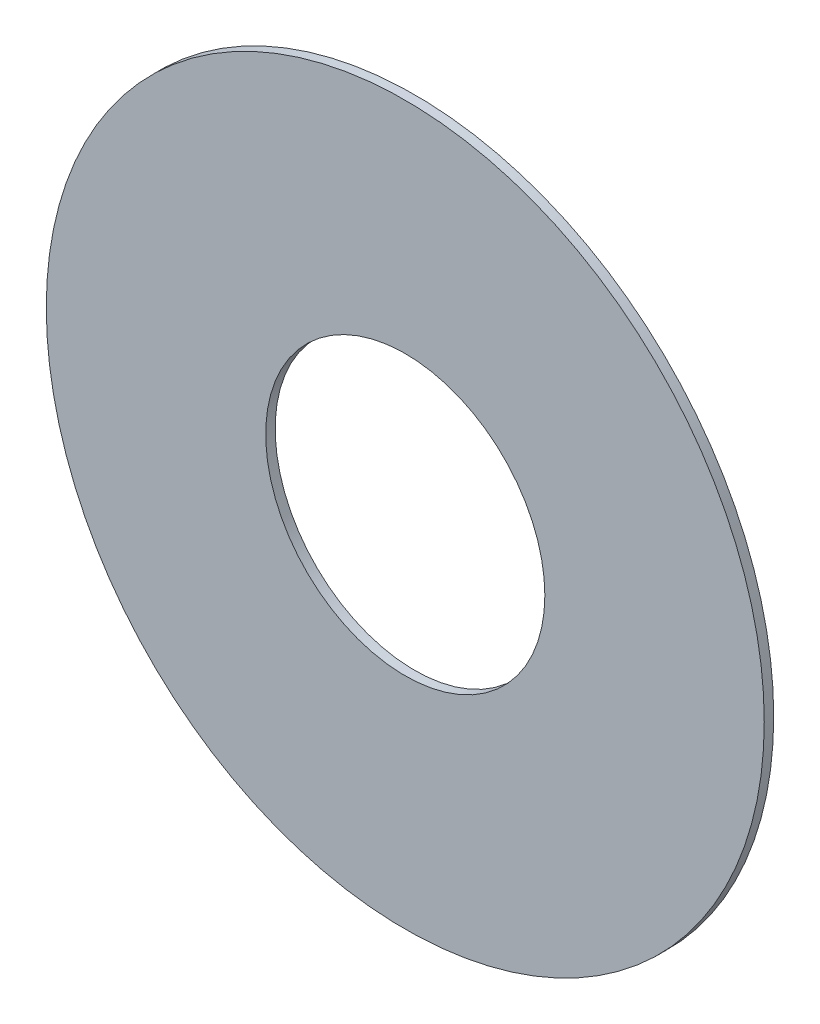
SolidWorks part; units mm, degrees
ref_plane "Спереди" through (0, 0, 0) normal (0, 0, 1) x (1, 0, 0)
ref_plane "Сверху" through (0, 0, 0) normal (0, 1, 0) x (1, 0, 0)
ref_plane "Справа" through (0, 0, 0) normal (1, 0, 0) x (0, 0, -1)
sketch "Эскиз1" plane through (0, 0, 0) normal (0, 0, 1) x (1, 0, 0)
  circle A0 centre (0, 0) radius 75.8769
  circle A1 centre (0, 0) radius 29.5
extrude "Printed_guard" add sketch "Эскиз1" along normal blind 2 from offset 40.5
